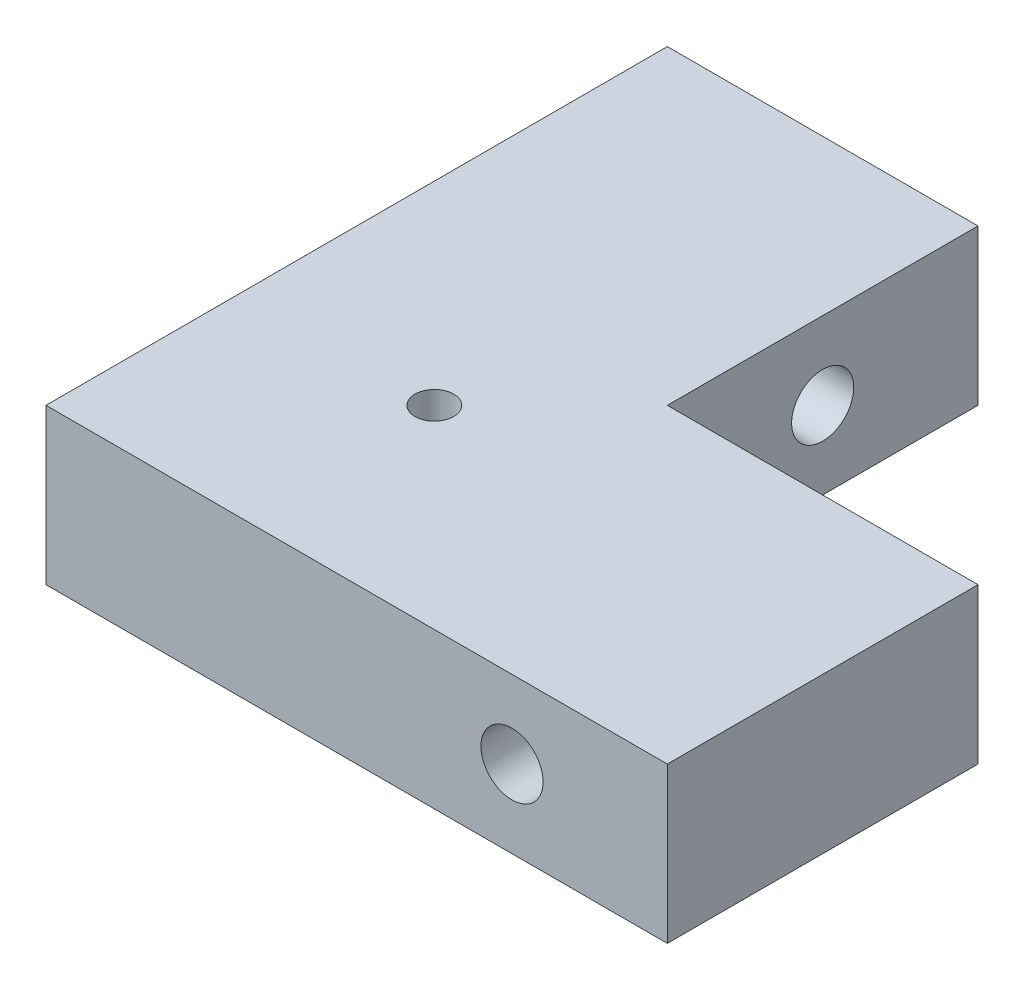
SolidWorks part; units mm, degrees
ref_plane "Plano frontal" through (0, 0, 0) normal (0, 0, 1) x (1, 0, 0)
ref_plane "Plano superior" through (0, 0, 0) normal (0, 1, 0) x (1, 0, 0)
ref_plane "Plano direito" through (0, 0, 0) normal (1, 0, 0) x (0, 0, -1)
sketch "Esboço1" plane through (0, 0, 0) normal (0, 1, 0) x (1, 0, 0)
  line L0 (-70, 36.3043) -> (-70, -43.6957)
  line L1 (-70, -43.6957) -> (10, -43.6957)
  line L2 (10, -43.6957) -> (10, -3.6957)
  line L3 (10, -3.6957) -> (-30, -3.6957)
  line L4 (-30, -3.6957) -> (-30, 36.3043)
  line L5 (-30, 36.3043) -> (-70, 36.3043)
  dimension "D1" = 40
  dimension "D2" = 40
  dimension "D3" = 40
extrude "Ressalto-extrusão1" add sketch "Esboço1" along normal blind 20 contours L0 L1 L2 L3 L4 L5
sketch "Esboço3" plane through (-30, 0, 0) normal (1, 0, 0) x (0, 0, -1)
  line L0 (36.3043, 10) -> (-3.6957, 10) construction
  line L1 (36.3043, 20) -> (36.3043, 0) construction
  line L2 (-3.6957, 20) -> (-3.6957, 0) construction
  circle A0 centre (16.3043, 10) radius 4
  dimension "D1" = 8
sketch "Esboço4" plane through (0, 0, 3.6957) normal (0, 0, -1) x (-1, 0, 0)
  line L0 (30, 10) -> (-10, 10) construction
  line L1 (-10, 20) -> (-10, 0) construction
  circle A0 centre (10, 10) radius 4
  dimension "D1" = 8
extrude "Corte-extrusão1" cut sketch "Esboço3" against normal through all
extrude "Corte-extrusão2" cut sketch "Esboço4" against normal through all
sketch "Esboço5" plane through (0, 0, 0) normal (0, -1, 0) x (1, 0, 0)
  line L0 (-70, -36.3043) -> (-70, 43.6957) construction
  line L1 (-70, 43.6957) -> (10, 43.6957) construction
  circle A0 centre (-45, 18.6957) radius 2.5
  dimension "D1" = 5
  dimension "D2" = 25
  dimension "D3" = 25
extrude "Corte-extrusão3" cut sketch "Esboço5" against normal through all
